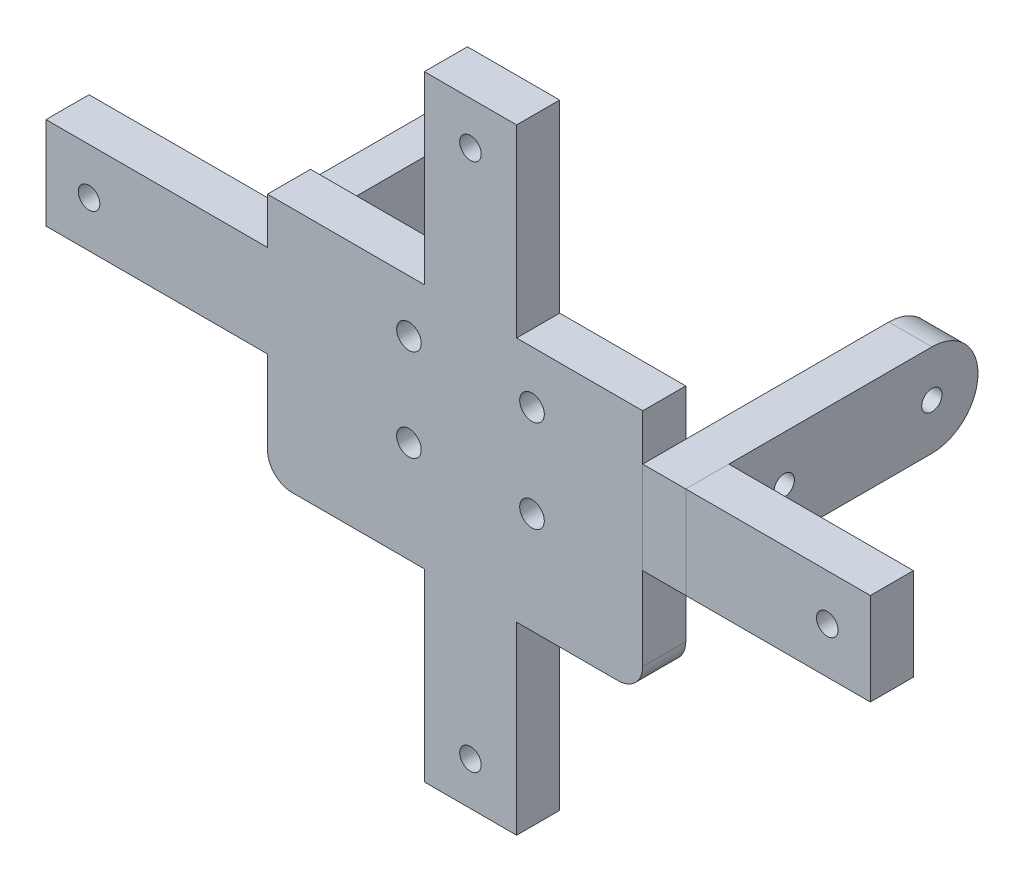
SolidWorks part; units mm, degrees
ref_plane "前视基准面" through (0, 0, 0) normal (0, 0, 1) x (1, 0, 0)
ref_plane "上视基准面" through (0, 0, 0) normal (0, 1, 0) x (1, 0, 0)
ref_plane "右视基准面" through (0, 0, 0) normal (1, 0, 0) x (0, 0, -1)
sketch "草图4" plane through (0, 0, 0) normal (0, 1, 0) x (1, 0, 0)
  line L0 (-33, 22.5) -> (28, 22.5)
  line L2 (-33, 29.5) -> (28, 29.5)
  line L3 (-33, 29.5) -> (-33, 22.5)
  line L5 (28, 29.5) -> (28, 22.5)
  line L6 (28, 38.5) -> (28, 49.5) construction
  dimension "D1" = 29.5
  dimension "D2" = 7
  dimension "D3" = 61
extrude "凸台-拉伸1" add sketch "草图4" against normal blind 6 from surface
sketch "草图5" plane through (0, 0, -29.5) normal (0, 0, -1) x (-1, 0, 0)
  line L0 (0, 4.5795) -> (0, 37.3232) construction
  line L1 (-28, 24.2) -> (33, 24.2) construction
  line L2 (-20, 24.2) -> (20, 24.2)
  line L3 (-20, 24.2) -> (-20, -9.8)
  line L4 (-20, -9.8) -> (20, -9.8)
  line L5 (20, 24.2) -> (20, -9.8)
  line L6 (-20, 24.2) -> (20, -9.8) construction
  line L7 (-20, -9.8) -> (20, 24.2) construction
  line L8 (-20, 14.2) -> (20, 14.2) construction
  circle A0 centre (-10, 21.7) radius 2
  circle A1 centre (10, 21.7) radius 2
  circle A4 centre (10, 6.7) radius 2
  circle A5 centre (-10, 6.7) radius 2
  point P3 (0, 7.2)
  dimension "D3" = 4
  dimension "D1" = 40
  dimension "D2" = 34
  dimension "D4" = 20
  dimension "D6" = 10
  dimension "D7" = 15
extrude "凸台-拉伸2" add sketch "草图5" against normal blind 7
sketch "草图7" plane through (0, 0, 0) normal (0, 1, 0) x (1, 0, 0)
  line L0 (-20, 22.5) -> (-20, 29.5) construction
  line L1 (20, 22.5) -> (-20, 22.5)
  line L2 (20, 22.5) -> (20, 2.5)
  line L3 (17, -0.5) -> (-17, -0.5)
  line L4 (-20, 22.5) -> (-20, 2.5)
  line L5 (-33, 22.5) -> (28, 22.5) construction
  line L6 (28, 22.5) -> (28, 29.5) construction
  circle A0 centre (10, 10) radius 4.1
  arc A1 (-17, -0.5) -> (-20, 2.5) centre (-17, 2.5) cw
  arc A2 (17, -0.5) -> (20, 2.5) centre (17, 2.5) ccw
  point P14 (20, -0.5)
  dimension "D1" = 8.2
  dimension "D3" = 3
  dimension "D2" = 23
  dimension "D4" = 8
extrude "凸台-拉伸3" add sketch "草图7" along normal blind 7 from surface at -9.8 starting at face at (0, -9.8, -26)
sketch "草图9" plane through (22, 25.2, -43.8683) normal (1, 0, 0) x (0, 0, 1)
  line L0 (16.2748, 10) -> (-40.3655, 10) construction
  line L2 (-18.6317, 2.5) -> (21.3683, 2.5)
  line L4 (-18.6317, 17.5) -> (21.3683, 17.5)
  line L5 (21.3683, 2.5) -> (21.3683, 17.5)
  line L6 (21.3683, 1) -> (21.3683, 28) construction
  circle A0 centre (-18.6317, 10) radius 1.65
  arc A1 (-18.6317, 17.5) -> (-18.6317, 2.5) centre (-18.6317, 10) ccw
  point P5 (-6.1317, 10)
  dimension "D1" = 3.3
  dimension "D3" = 7.5
  dimension "D2" = 15
  dimension "D4" = 40
extrude "凸台-拉伸4" add sketch "草图9" against normal blind 6 from surface at -55 separate body starting at face at (-33, 27.2, -26)
sketch "草图10" plane through (0, 0, 0) normal (0, 0, 1) x (1, 0, 0)
  line L8 (-20, -2.8) -> (-20, 24.2) construction
  line L9 (-33, 30.2) -> (28, 30.2) construction
  line L10 (-33, 30.2) -> (-20, 30.2)
  line L11 (-20, 30.2) -> (-20, -9.8)
  line L12 (17, -9.8) -> (-17, -9.8) construction
  line L13 (-20, -9.8) -> (-29, -9.8)
  line L14 (-33, 30.2) -> (-33, -5.8)
  line L15 (-33, 22.7) -> (-33, 7.7) construction
  arc A1 (-29, -9.8) -> (-33, -5.8) centre (-29, -5.8) cw
  dimension "D1" = 4
extrude "凸台-拉伸5" add sketch "草图10" against normal blind 7 from surface at -22.5 starting at face at (12, 6.7, -22.5)
sketch "草图14" plane through (0, 0, 0) normal (1, 0, 0) x (0, 0, -1)
  line L0 (22.5, 30.2) -> (29.5, 30.2) construction
  line L5 (22.5, 24.2) -> (22.5, 30.2) construction
  line L10 (22.5, 24.2) -> (22.5, -2.8) construction
  line L11 (22.5, 22.7) -> (62.5, 22.7)
  line L12 (76.2455, 15.2) -> (22.5, 15.2) construction
  line L13 (22.5, 22.7) -> (22.5, 7.7)
  line L15 (22.5, 7.7) -> (62.5, 7.7)
  line L17 (22.5, 22.7) -> (62.5, 7.7) construction
  line L18 (22.5, 7.7) -> (62.5, 22.7) construction
  circle A0 centre (38.5, 15.2) radius 1.65
  arc A1 (62.5, 7.7) -> (62.5, 22.7) centre (62.5, 15.2) ccw
  circle A2 centre (62.5, 15.2) radius 1.65
  point P0 (42.5, 15.2)
  dimension "D3" = 3.3
  dimension "D4" = 40
  dimension "D5" = 16
  dimension "D6" = 40
  dimension "D1" = 15
  dimension "D2" = 15
extrude "凸台-拉伸8" add sketch "草图14" along normal blind 7 from surface at 28 separate body starting at face at (28, 27.2, -26)
sketch "草图17" plane through (-33, 0, 0) normal (1, 0, 0) x (0, 0, -1)
  circle A0 centre (62.5, 15.2) radius 3
  circle A1 centre (62.5, 15.2) radius 1.5
  dimension "D1" = 6
extrude "凸台-拉伸11" add sketch "草图17" along normal blind 0.5
sketch "草图21" plane through (0, 0, 0) normal (0, 0, 1) x (1, 0, 0)
  line L1 (7.5, 30.2) -> (-7.5, 30.2)
  line L2 (7.5, 30.2) -> (7.5, 60.2)
  line L3 (7.5, 60.2) -> (-7.5, 60.2)
  line L4 (-7.5, 30.2) -> (-7.5, 60.2)
  line L6 (-39, 22.7) -> (-69, 22.7)
  line L7 (-39, 22.7) -> (-39, 7.7)
  line L8 (-39, 7.7) -> (-69, 7.7)
  line L9 (-69, 22.7) -> (-69, 7.7)
  line L10 (35, 22.7) -> (65, 22.7)
  line L11 (35, 22.7) -> (35, 7.7)
  line L12 (35, 7.7) -> (65, 7.7)
  line L13 (65, 22.7) -> (65, 7.7)
  line L15 (-7.5, -9.8) -> (7.5, -9.8)
  line L16 (-7.5, -9.8) -> (-7.5, -39.8)
  line L17 (-7.5, -39.8) -> (7.5, -39.8)
  line L18 (7.5, -9.8) -> (7.5, -39.8)
  line L20 (-69, 15.2) -> (-39, 15.2) construction
  line L21 (0, 80.5223) -> (0, -64.0793) construction
  line L22 (35, 15.2) -> (65, 15.2) construction
  line L24 (35, 22.7) -> (28, 22.7) construction
  line L25 (20, -9.8) -> (20, 24.2)
  line L26 (20, 24.2) -> (28, 24.2)
  line L27 (28, 24.2) -> (28, -5.8)
  line L28 (24, -9.8) -> (20, -9.8)
  line L29 (35, 7.7) -> (35, 22.7) construction
  line L30 (-33, 30.2) -> (28, 30.2) construction
  line L31 (-33, -5.8) -> (-33, 7.7) construction
  line L33 (-29, -9.8) -> (-20, -9.8) construction
  line L34 (-39, 7.7) -> (-39, 22.7) construction
  line L35 (-39, 22.7) -> (-33, 22.7) construction
  line L36 (-39, 7.7) -> (-33, 7.7) construction
  circle A0 centre (-62, 15.2) radius 1.75
  circle A1 centre (0, 53.2) radius 1.75
  circle A2 centre (0, -32.8) radius 1.75
  circle A3 centre (58, 15.2) radius 1.75
  arc A4 (24, -9.8) -> (28, -5.8) centre (24, -5.8) ccw
  dimension "D9" = 3.5
  dimension "D7" = 4
  dimension "D1" = 30
  dimension "D2" = 30
  dimension "D3" = 30
  dimension "D4" = 15
  dimension "D5" = 30
  dimension "D6" = 15
  dimension "D8" = 15
  dimension "D10" = 7
  dimension "D11" = 7
  dimension "D12" = 7
  dimension "D13" = 7
  dimension "D14" = 33
extrude "凸台-拉伸12" add sketch "草图21" against normal blind 7 from surface at -22.5 starting at face at (-14.1406, 10.5978, -22.5)
sketch "草图22" plane through (0, 0, -22.5) normal (0, 0, 1) x (1, 0, 0)
  line L1 (20, -9.8) -> (-20, -9.8)
  line L2 (20, -9.8) -> (20, -2.8)
  line L3 (20, -2.8) -> (-20, -2.8)
  line L4 (-20, -9.8) -> (-20, -2.8)
extrude "切除-拉伸1" cut sketch "草图22" along normal up to surface (23 mm away) up to face at (0, -6.3, 0.5)
